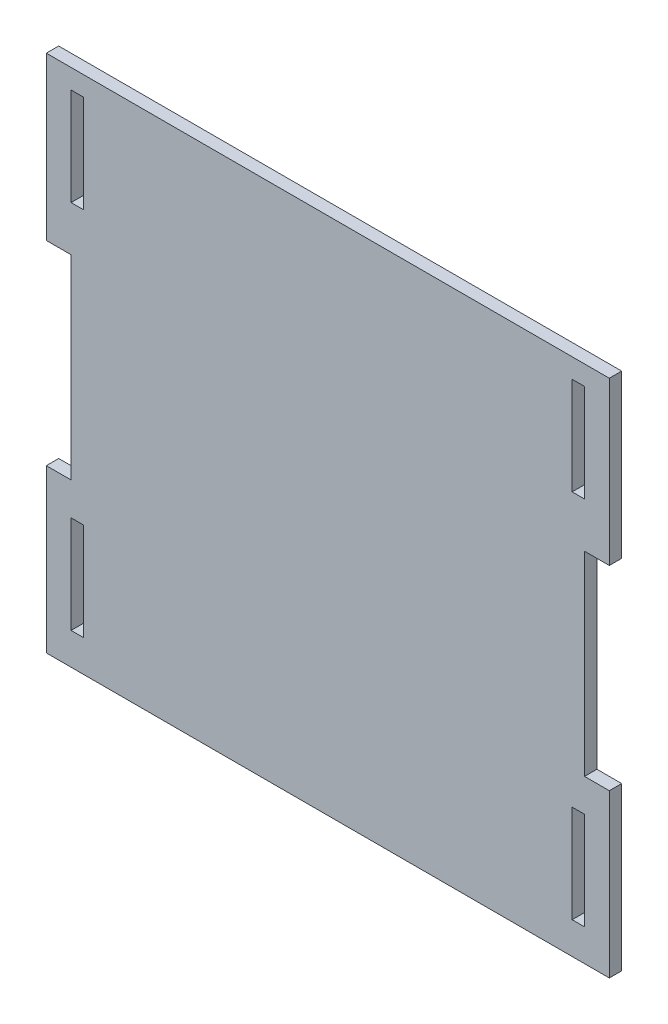
SolidWorks part; units mm, degrees
ref_plane "Front Plane" through (0, 0, 0) normal (0, 0, 1) x (1, 0, 0)
ref_plane "Top Plane" through (0, 0, 0) normal (0, 1, 0) x (1, 0, 0)
ref_plane "Right Plane" through (0, 0, 0) normal (1, 0, 0) x (0, 0, -1)
sketch "Sketch1" plane through (0, 0, 0) normal (0, 0, 1) x (1, 0, 0)
  line L0 (0, 91.5875) -> (6.35, 91.5875)
  line L1 (0, 0) -> (144.35, 0)
  line L2 (0, 0) -> (0, 41.5875)
  line L3 (0, 133.175) -> (144.35, 133.175)
  line L4 (144.35, 0) -> (144.35, 41.5875)
  line L5 (6.35, 91.5875) -> (6.35, 41.5875)
  line L6 (6.35, 41.5875) -> (0, 41.5875)
  line L7 (144.35, 91.5875) -> (138, 91.5875)
  line L8 (138, 91.5875) -> (138, 41.5875)
  line L9 (138, 41.5875) -> (144.35, 41.5875)
  line L10 (0, 91.5875) -> (0, 133.175)
  line L11 (144.35, 91.5875) -> (144.35, 133.175)
  line L13 (6.35, 103.175) -> (9.525, 103.175)
  line L14 (6.35, 103.175) -> (6.35, 128.175)
  line L15 (6.35, 128.175) -> (9.525, 128.175)
  line L16 (9.525, 103.175) -> (9.525, 128.175)
  line L17 (138, 103.175) -> (134.825, 103.175)
  line L18 (138, 103.175) -> (138, 128.175)
  line L19 (138, 128.175) -> (134.825, 128.175)
  line L20 (134.825, 103.175) -> (134.825, 128.175)
  line L21 (6.35, 33.175) -> (9.525, 33.175)
  line L22 (6.35, 33.175) -> (6.35, 8.175)
  line L23 (6.35, 8.175) -> (9.525, 8.175)
  line L24 (9.525, 33.175) -> (9.525, 8.175)
  line L25 (138, 33.175) -> (134.825, 33.175)
  line L26 (138, 33.175) -> (138, 8.175)
  line L27 (138, 8.175) -> (134.825, 8.175)
  line L28 (134.825, 33.175) -> (134.825, 8.175)
  dimension "D1" = 144.35
  dimension "D2" = 133.175
  dimension "D3" = 50
  dimension "D4" = 50
  dimension "D5" = 6.35
  dimension "D6" = 25
  dimension "D7" = 25
  dimension "D8" = 25
  dimension "D9" = 25
  dimension "D10" = 3.175
  dimension "D11" = 3.175
  dimension "D12" = 3.175
  dimension "D13" = 3.175
  dimension "D14" = 8.175
  dimension "D15" = 8.175
  dimension "D16" = 5
  dimension "D17" = 5
extrude "Boss-Extrude1" add sketch "Sketch1" along normal blind 3.175
